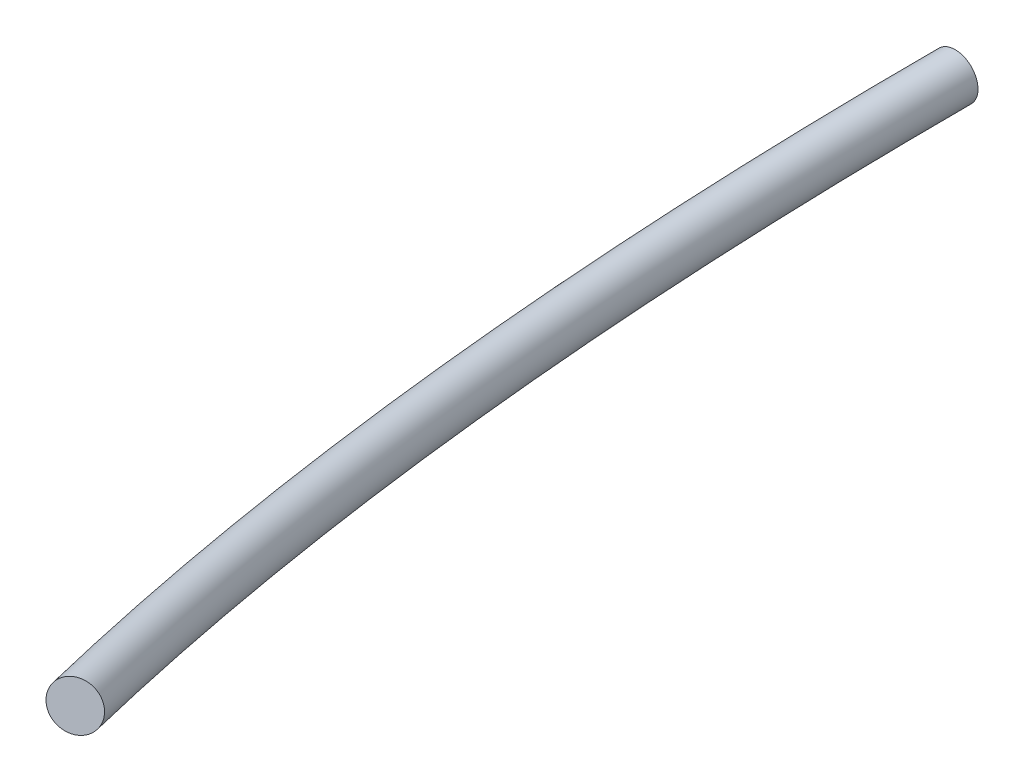
SolidWorks part; units mm, degrees
ref_plane "Front" through (0, 0, 0) normal (0, 0, 1) x (1, 0, 0)
ref_plane "Top" through (0, 0, 0) normal (0, 1, 0) x (1, 0, 0)
ref_plane "Right" through (0, 0, 0) normal (1, 0, 0) x (0, 0, -1)
sketch "Sketch1" plane through (0, 0, 0) normal (0, 0, 1) x (1, 0, 0)
  circle A0 centre (715.1784, -11440.7421) radius 50.8
ref_plane "Plane2" through (4326.7847, -9855.1022, 0) normal (-0.402, 0.9156, 0) x (0.6981, 0.3065, -0.6471)
sketch "Sketch2" plane through (4326.7847, -9855.1022, 0) normal (-0.402, 0.9156, 0) x (0.6981, 0.3065, -0.6471)
  line L0 (-4198.2999, 441.3566) -> (-4583.8099, -707.9386) construction
  line L1 (-3007.2863, 2552.2898) -> (-3538.3639, 1926.537) construction
  line L2 (-3007.2863, 2552.2898) -> (-4198.2999, 441.3566) construction
  line L3 (-3703.3923, 1553.5825) -> (-3602.7931, 1496.8232) construction
  arc A0 (-3007.2863, 2552.2898) -> (-4198.2999, 441.3566) centre (1883.7757, -1598.7642) ccw
  point P3 (-4126.2087, 644.8542)
  point P5 (-3794.5258, 1386.3034)
  point P6 (-3371.8105, 2079.8972)
  point P7 (-3703.3923, 1553.5825)
  dimension "D1" = 2438.4
  dimension "D2" = 215.9
  dimension "D3" = 812.8
  dimension "D4" = 812.8
  dimension "D5" = 1219.2
  dimension "D6" = 115.5068
sweep "Sweep1" add profiles "Sketch1" path "Sketch2"
